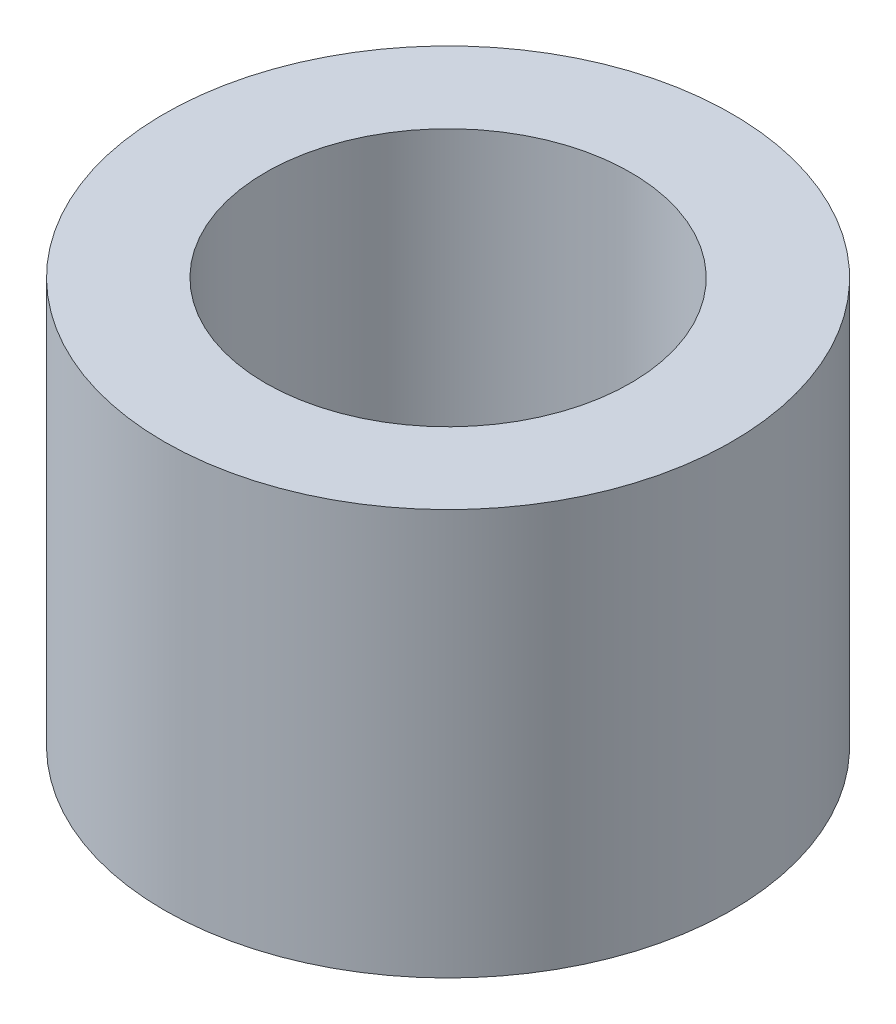
SolidWorks part; units mm, degrees
ref_plane "Front Plane" through (0, 0, 0) normal (0, 0, 1) x (1, 0, 0)
ref_plane "Top Plane" through (0, 0, 0) normal (0, 1, 0) x (1, 0, 0)
ref_plane "Right Plane" through (0, 0, 0) normal (1, 0, 0) x (0, 0, -1)
sketch "Sketch1" plane through (0, 0, 0) normal (0, 1, 0) x (1, 0, 0)
  circle A0 centre (0, 0) radius 3.5
  dimension "7.5" = 7
extrude "Boss-Extrude1" add sketch "Sketch1" along normal blind 5
sketch "Sketch2" plane through (0, 5, 0) normal (0, 1, 0) x (1, 0, 0)
  circle A0 centre (0, 0) radius 2.25
  dimension "4" = 4.5
extrude "Cut-Extrude1" cut sketch "Sketch2" against normal through all
